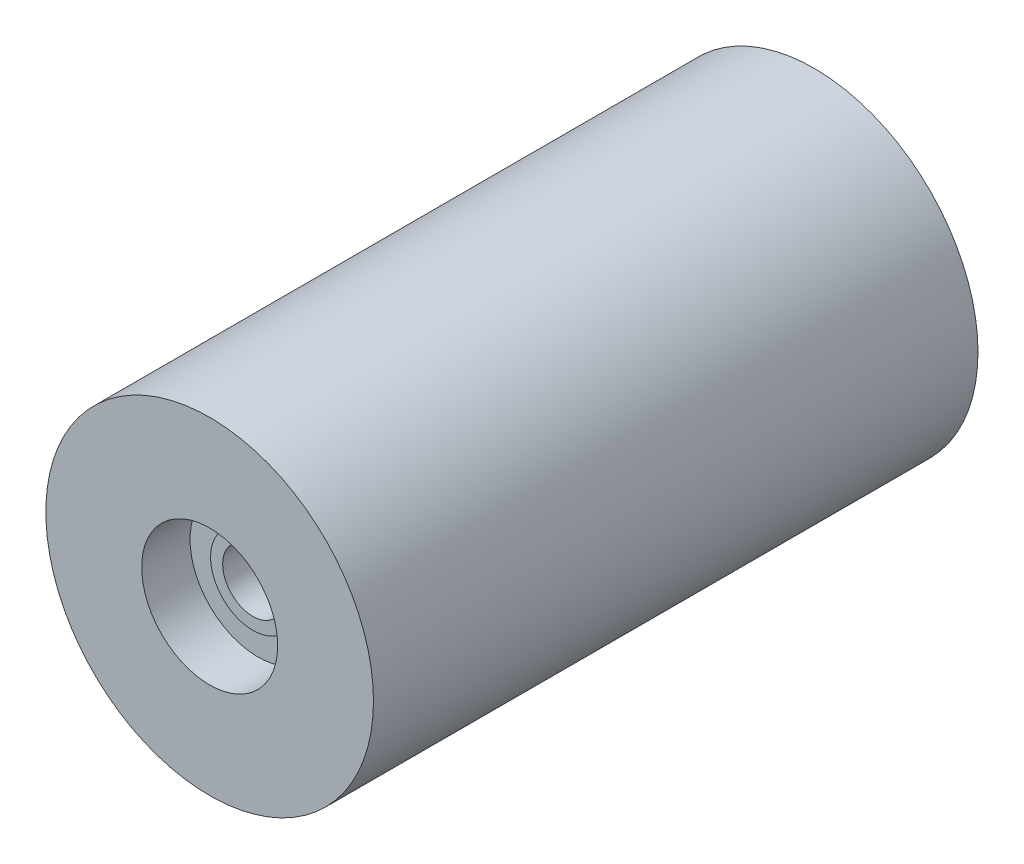
SolidWorks part; units mm, degrees
ref_plane "Front Plane" through (0, 0, 0) normal (0, 0, 1) x (1, 0, 0)
ref_plane "Top Plane" through (0, 0, 0) normal (0, 1, 0) x (1, 0, 0)
ref_plane "Right Plane" through (0, 0, 0) normal (1, 0, 0) x (0, 0, -1)
sketch "Sketch1" plane through (0, 0, 0) normal (0, 0, 1) x (1, 0, 0)
  circle A0 centre (0, 0) radius 5
  circle A1 centre (0, 0) radius 27.1
  dimension "D1" = 10
  dimension "D2" = 54.2
extrude "Boss-Extrude1" add sketch "Sketch1" along normal blind 100
sketch "Sketch2" plane through (0, 0, 100) normal (0, 0, 1) x (1, 0, 0)
  circle A0 centre (0, 0) radius 11.25
  circle A1 centre (0, 0) radius 7
  circle M2 centre (0, 0) radius 5
  dimension "D1" = 22.5
  dimension "D2" = 14
extrude "Cut-Extrude1" cut sketch "Sketch2" against normal blind 7.15 contours A1 M2
sketch "Sketch3" plane through (0, 0, 100) normal (0, 0, 1) x (1, 0, 0)
  circle A0 centre (0, 0) radius 7
  circle A1 centre (0, 0) radius 11.25
  dimension "D1" = 22.5
  dimension "D2" = 14
extrude "Cut-Extrude2" cut sketch "Sketch3" against normal blind 8
sketch "Sketch4" plane through (0, 0, 0) normal (0, 0, -1) x (-1, 0, 0)
  circle A0 centre (0, 0) radius 7
  dimension "D1" = 14
extrude "Cut-Extrude3" cut sketch "Sketch4" against normal blind 7.15
sketch "Sketch5" plane through (0, 0, 0) normal (0, 0, -1) x (-1, 0, 0)
  circle A0 centre (0, 0) radius 7
  circle A1 centre (0, 0) radius 11.25
  dimension "D1" = 22.5
extrude "Cut-Extrude4" cut sketch "Sketch5" against normal blind 8
